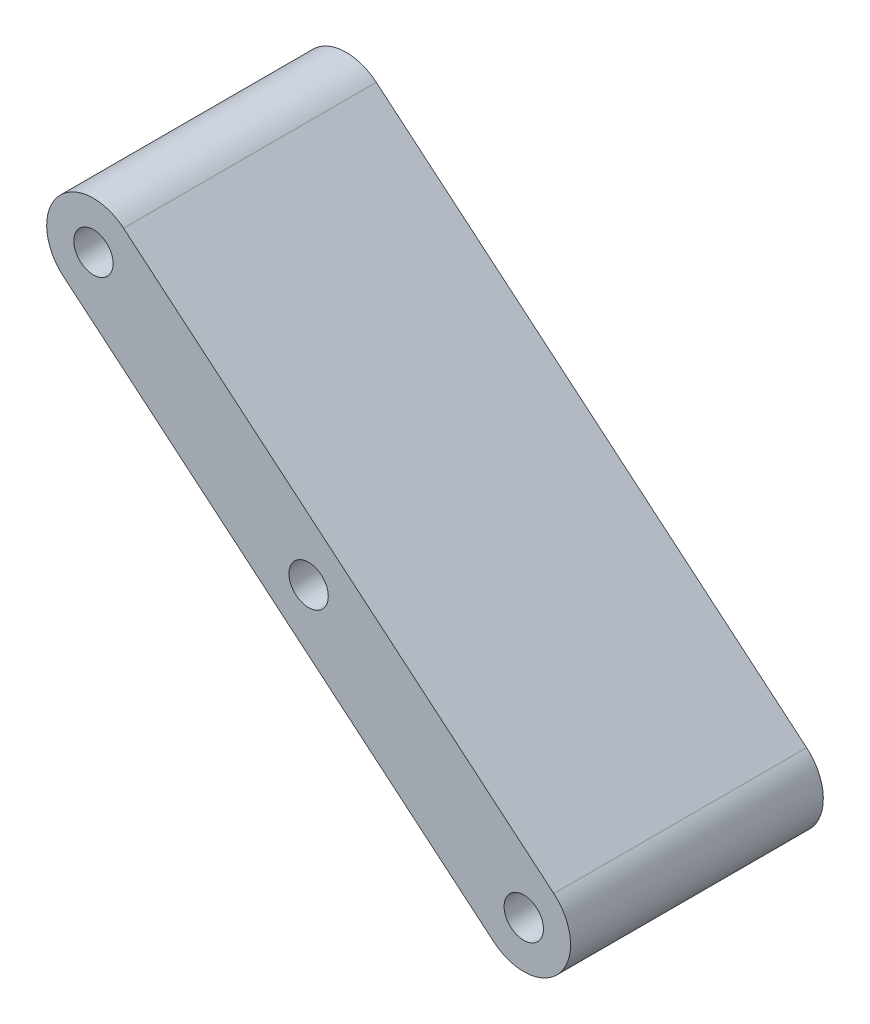
SolidWorks part; units mm, degrees
material "ABS"
ref_plane "Front Plane" through (0, 0, 0) normal (0, 0, 1) x (1, 0, 0)
ref_plane "Top Plane" through (0, 0, 0) normal (0, 1, 0) x (1, 0, 0)
ref_plane "Right Plane" through (0, 0, 0) normal (1, 0, 0) x (0, 0, -1)
sketch "Sketch1" plane through (0, 0, 10) normal (0, 0, 1) x (1, 0, 0)
  line L0 (44.6638, -44.0044) -> (90.6265, -82.5717)
  line L1 (51.0917, -36.344) -> (97.0544, -74.9113)
  circle A0 centre (47.8778, -40.1742) radius 2.1
  circle A1 centre (70.8591, -59.4579) radius 2.1
  circle A2 centre (93.8404, -78.7415) radius 2.1
  arc A3 (51.0917, -36.344) -> (44.6638, -44.0044) centre (47.8778, -40.1742) ccw
  arc A4 (90.6265, -82.5717) -> (97.0544, -74.9113) centre (93.8404, -78.7415) ccw
  dimension "D1" = 4.2
  dimension "D2" = 4.2
  dimension "D3" = 4.2
  dimension "D4" = 10
  dimension "D5" = 10
extrude "Boss-Extrude1" add sketch "Sketch1" along normal blind 27
equation "\"thighLength\"=185"
equation "\"legLength\"=200"
equation "\"m3Thru\"=3.2"
equation "\"m4Thru\"=4.3"
equation "\"m3Insert\"=4.2"
equation "\"m4Insert\"=5.3"
equation "\"shoulder5mm\"=5.1"
equation "\"6706out\"=37.125"
equation "\"6706in\"=30"
equation "\"6904out\"=30.125"
equation "\"6904in\"=17"
equation "\"D1@Sketch1\"=\"m3Insert\" "
equation "\"D2@Sketch1\"=\"m3Insert\" "
equation "\"D3@Sketch1\"=\"m3Insert\" "
